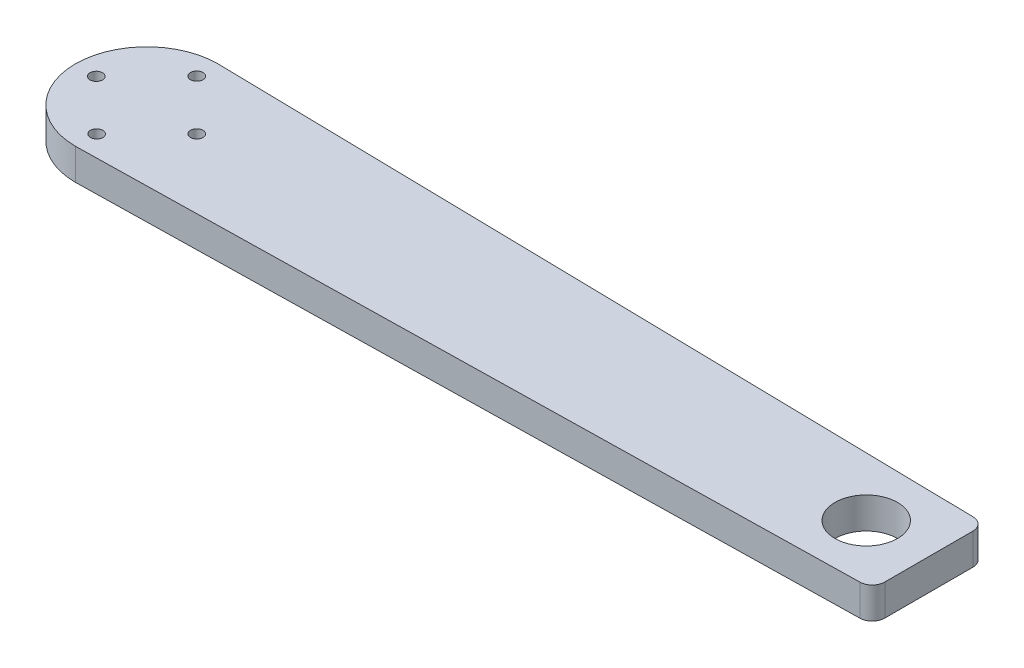
SolidWorks part; units mm, degrees
ref_plane "Alzado" through (0, 0, 0) normal (0, 0, 1) x (1, 0, 0)
ref_plane "Planta" through (0, 0, 0) normal (0, 1, 0) x (1, 0, 0)
ref_plane "Vista lateral" through (0, 0, 0) normal (1, 0, 0) x (0, 0, -1)
sketch "Croquis1" plane through (0, 0, 0) normal (0, 1, 0) x (1, 0, 0)
  line L0 (0, 0) -> (125, 0) construction
  line L1 (125, -9) -> (125, 9)
  line L2 (125, 9) -> (0, 11.4)
  line L3 (0, 8) -> (0, -8) construction
  line L4 (0, -11.4) -> (125, -9)
  line L6 (-8, -0.0552) -> (8, 0) construction
  arc A0 (0, 11.4) -> (0, -11.4) centre (0, 0) ccw
  circle A1 centre (115, 0) radius 5
  circle A2 centre (-8, -0.0552) radius 1
  circle A3 centre (0, -8) radius 1
  circle A4 centre (0, 8) radius 1
  circle A5 centre (8, 0) radius 1
  dimension "D1" = 9
  dimension "D3" = 10
  dimension "D6" = 8
  dimension "D8" = 115
  dimension "D2" = 9
  dimension "D4" = 8
  dimension "D5" = 8
  dimension "D7" = 8
extrude "Saliente-Extruir1" add sketch "Croquis1" along normal blind 5
fillet "Redondeo1" radius 2 2 edges at (125, 2.5, 9) (125, 2.5, -9)
